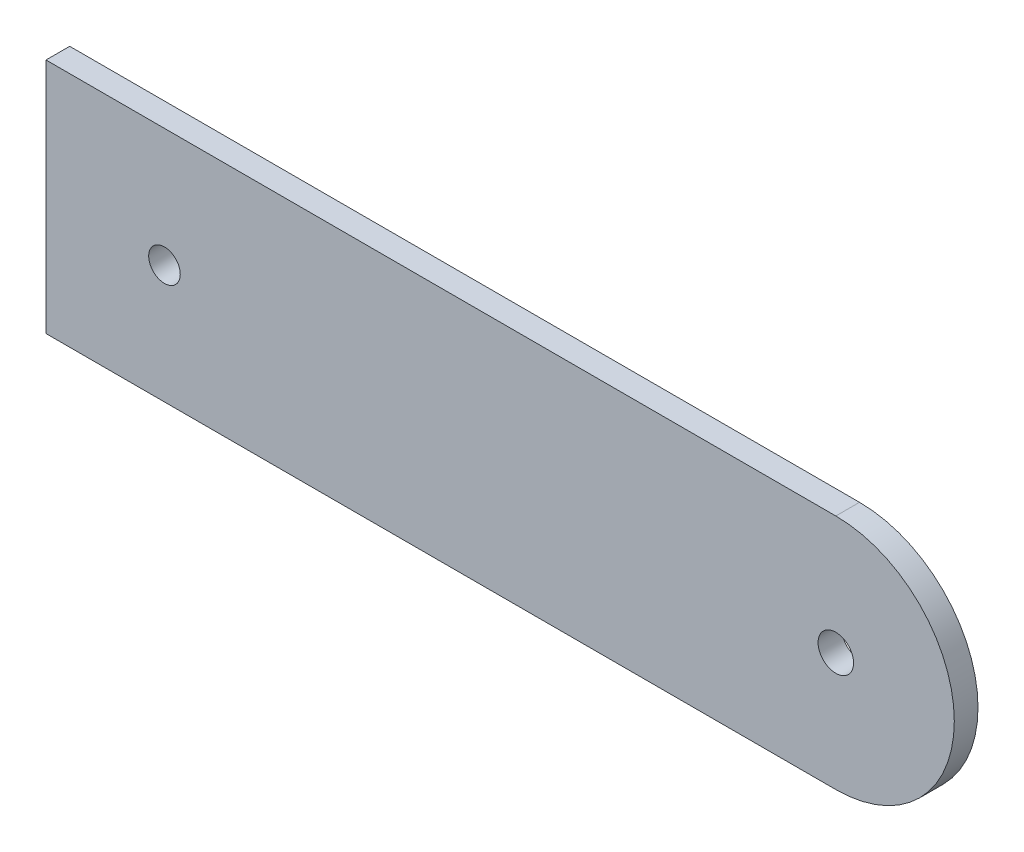
SolidWorks part; units mm, degrees
ref_plane "Front Plane" through (0, 0, 0) normal (0, 0, 1) x (1, 0, 0)
ref_plane "Top Plane" through (0, 0, 0) normal (0, 1, 0) x (1, 0, 0)
ref_plane "Right Plane" through (0, 0, 0) normal (1, 0, 0) x (0, 0, -1)
sketch "Croquis1" plane through (0, 0, 0) normal (0, 0, 1) x (1, 0, 0)
  line L0 (0, 0) -> (100, 0)
  line L1 (0, 0) -> (0, 30)
  line L2 (0, 30) -> (100, 30)
  line L3 (15, 15) -> (0, 15) construction
  arc A0 (100, 30) -> (100, 0) centre (100, 15) cw
  circle A1 centre (15, 15) radius 2
  circle A2 centre (100, 15) radius 2.25
  dimension "D1" = 30
  dimension "D2" = 4
  dimension "D5" = 4.5
  dimension "D3" = 100
  dimension "D4" = 15
extrude "Saliente-Extruir2" add sketch "Croquis1" along normal blind 3
